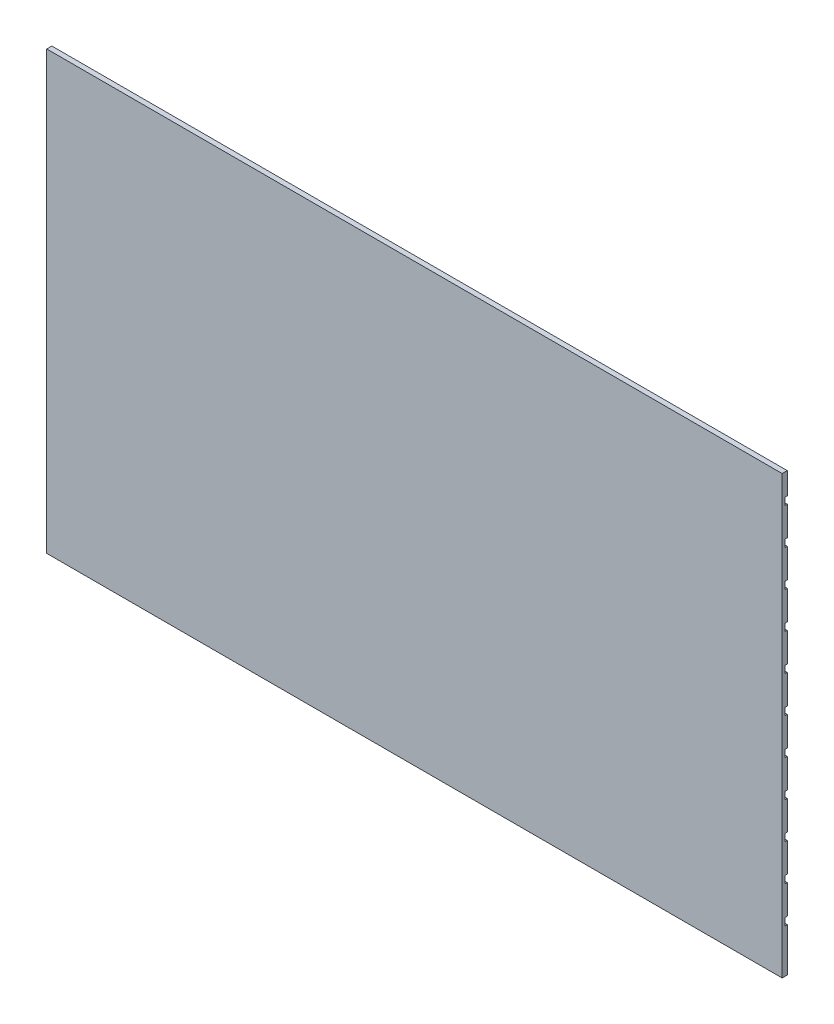
SolidWorks part; units mm, degrees
ref_plane "Front Plane" through (0, 0, 0) normal (0, 0, 1) x (1, 0, 0)
ref_plane "Top Plane" through (0, 0, 0) normal (0, 1, 0) x (1, 0, 0)
ref_plane "Right Plane" through (0, 0, 0) normal (1, 0, 0) x (0, 0, -1)
sketch "Sketch2" plane through (0, 0, 0) normal (1, 0, 0) x (0, 0, -1)
  line L1 (0, 0) -> (17.78, 0)
  line L2 (0, 0) -> (0, -1524)
  line L3 (0, -1524) -> (17.78, -1524)
  line L4 (17.78, 0) -> (17.78, -1524)
  dimension "D1" = 17.78
  dimension "D2" = 1524
extrude "Boss-Extrude1" add sketch "Sketch2" along normal blind 2565.4
sketch "Sketch3" plane through (0, 0, -17.78) normal (0, 0, -1) x (-1, 0, 0)
  line L0 (-2565.4, -1524) -> (-2565.4, 0) construction
  line L1 (-2565.4, -76.2) -> (0, -76.2)
  line L2 (-2565.4, -76.2) -> (-2565.4, -101.6)
  line L3 (-2565.4, -101.6) -> (0, -101.6)
  line L4 (0, -76.2) -> (0, -101.6)
  line L5 (0, -1524) -> (0, 0) construction
  line L6 (-2565.4, 0) -> (0, 0) construction
  line L7 (-2565.4, -228.6) -> (0, -228.6)
  line L8 (-2565.4, -203.2) -> (0, -203.2)
  line L9 (-2565.4, -203.2) -> (-2565.4, -228.6)
  line L10 (0, -203.2) -> (0, -228.6)
  line L11 (-2565.4, -355.6) -> (0, -355.6)
  line L12 (-2565.4, -330.2) -> (0, -330.2)
  line L13 (-2565.4, -330.2) -> (-2565.4, -355.6)
  line L14 (0, -330.2) -> (0, -355.6)
  line L15 (-2565.4, -482.6) -> (0, -482.6)
  line L16 (-2565.4, -457.2) -> (0, -457.2)
  line L17 (-2565.4, -457.2) -> (-2565.4, -482.6)
  line L18 (0, -457.2) -> (0, -482.6)
  line L19 (-2565.4, -609.6) -> (0, -609.6)
  line L20 (-2565.4, -584.2) -> (0, -584.2)
  line L21 (-2565.4, -584.2) -> (-2565.4, -609.6)
  line L22 (0, -584.2) -> (0, -609.6)
  line L23 (-2565.4, -736.6) -> (0, -736.6)
  line L24 (-2565.4, -711.2) -> (0, -711.2)
  line L25 (-2565.4, -711.2) -> (-2565.4, -736.6)
  line L26 (0, -711.2) -> (0, -736.6)
  line L27 (-2565.4, -863.6) -> (0, -863.6)
  line L28 (-2565.4, -838.2) -> (0, -838.2)
  line L29 (-2565.4, -838.2) -> (-2565.4, -863.6)
  line L30 (0, -838.2) -> (0, -863.6)
  line L31 (-2565.4, -990.6) -> (0, -990.6)
  line L32 (-2565.4, -965.2) -> (0, -965.2)
  line L33 (-2565.4, -965.2) -> (-2565.4, -990.6)
  line L34 (0, -965.2) -> (0, -990.6)
  line L35 (-2565.4, -1117.6) -> (0, -1117.6)
  line L36 (-2565.4, -1092.2) -> (0, -1092.2)
  line L37 (-2565.4, -1092.2) -> (-2565.4, -1117.6)
  line L38 (0, -1092.2) -> (0, -1117.6)
  line L39 (-2565.4, -1244.6) -> (0, -1244.6)
  line L40 (-2565.4, -1219.2) -> (0, -1219.2)
  line L41 (-2565.4, -1219.2) -> (-2565.4, -1244.6)
  line L42 (0, -1219.2) -> (0, -1244.6)
  line L43 (-2565.4, -1371.6) -> (0, -1371.6)
  line L44 (-2565.4, -1346.2) -> (0, -1346.2)
  line L45 (-2565.4, -1346.2) -> (-2565.4, -1371.6)
  line L46 (0, -1346.2) -> (0, -1371.6)
  dimension "D1" = 25.4
  dimension "D2" = 76.2
  dimension "D3" = 11
extrude "Cut-Extrude1" cut sketch "Sketch3" against normal blind 7.62
